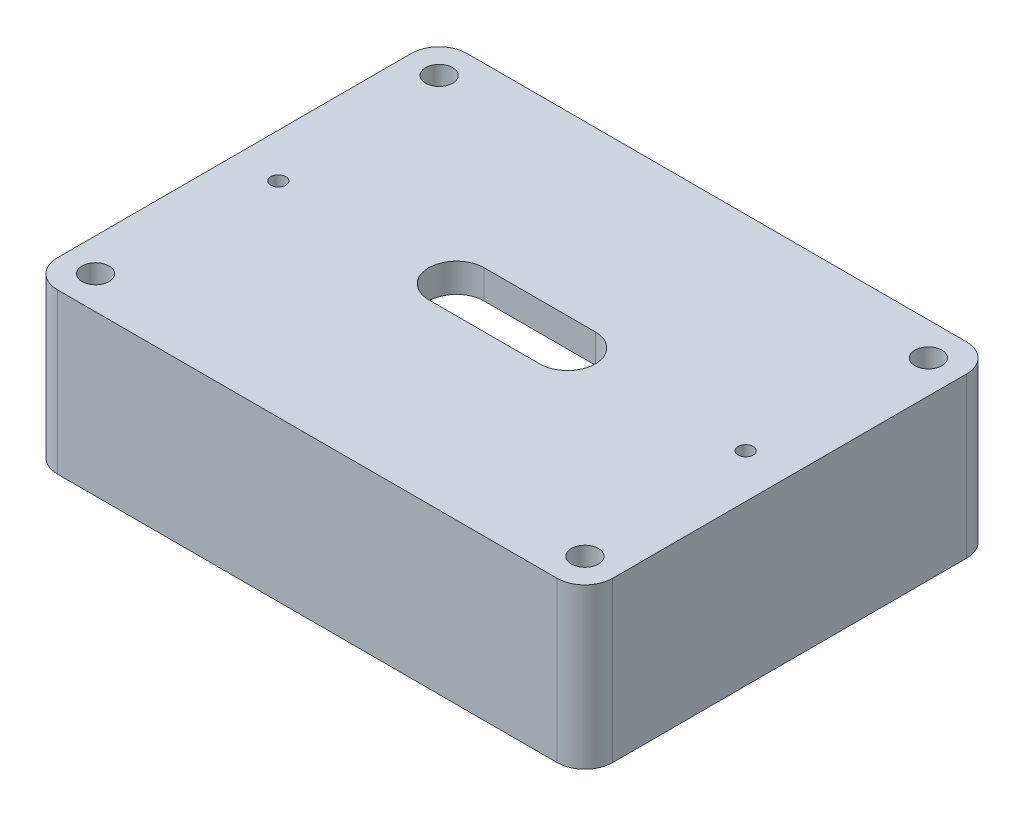
SolidWorks part; units mm, degrees
ref_plane "Front Plane" through (0, 0, 0) normal (0, 0, 1) x (1, 0, 0)
ref_plane "Top Plane" through (0, 0, 0) normal (0, 1, 0) x (1, 0, 0)
ref_plane "Right Plane" through (0, 0, 0) normal (1, 0, 0) x (0, 0, -1)
sketch "Sketch1" plane through (0, 0, 0) normal (0, 1, 0) x (1, 0, 0)
  line L1 (-40, -29.5) -> (40, -29.5)
  line L2 (-40, -29.5) -> (-40, 29.5)
  line L3 (-40, 29.5) -> (40, 29.5)
  line L4 (40, -29.5) -> (40, 29.5)
  line L5 (-40, -29.5) -> (40, 29.5) construction
  line L6 (-40, 29.5) -> (40, -29.5) construction
  point P0 (0, 0)
  dimension "D1" = 80
  dimension "D2" = 59
extrude "Boss-Extrude1" add sketch "Sketch1" along normal blind 23
sketch "Sketch2" plane through (0, 23, 0) normal (0, 1, 0) x (1, 0, 0)
  line L0 (40, -29.5) -> (40, 29.5) construction
  line L1 (40, 29.5) -> (-40, 29.5) construction
  line L2 (-40, -29.5) -> (40, -29.5) construction
  line L3 (-40, 29.5) -> (-40, -29.5) construction
  circle A0 centre (35.25, 24.75) radius 1.95
  circle A1 centre (35.25, -24.75) radius 1.95
  circle A2 centre (-35.25, 24.75) radius 1.95
  circle A3 centre (-35.25, -24.75) radius 1.95
  dimension "D1" = 4.75
  dimension "D4" = 4.75
  dimension "D7" = 4.75
  dimension "D10" = 4.75
  dimension "D3" = 4.75
  dimension "D5" = 4.75
  dimension "D8" = 4.75
  dimension "D11" = 4.75
extrude "Cut-Extrude1" cut sketch "Sketch2" against normal blind 23
shell "Shell2" thickness 4.15
sketch "Sketch3" plane through (0, 23, 0) normal (0, 1, 0) x (1, 0, 0)
  line L0 (8, 0) -> (-8, 0) construction
  line L1 (8, -4) -> (-8, -4)
  line L2 (8, 4) -> (-8, 4)
  line L3 (40, -29.5) -> (40, 29.5) construction
  line L4 (-40, 29.5) -> (-40, -29.5) construction
  arc A0 (8, -4) -> (8, 4) centre (8, 0) ccw
  arc A1 (-8, 4) -> (-8, -4) centre (-8, 0) ccw
  point P3 (0, 0)
  dimension "D1" = 32
  dimension "D2" = 32
extrude "Cut-Extrude2" cut sketch "Sketch3" against normal blind 23
sketch "Sketch4" plane through (-40, 0, 0) normal (-1, 0, 0) x (0, 0, 1)
  line L5 (-29.5, 23) -> (29.5, 23) construction
  line L6 (5, 0) -> (-5, 0)
  line L10 (5, 0) -> (5, 3)
  line L11 (5, 3) -> (-5, 3)
  line L12 (-5, 0) -> (-5, 3)
  line L13 (5, 0) -> (-5, 3) construction
  line L14 (5, 3) -> (-5, 0) construction
  line L15 (-29.5, 23) -> (-29.5, 0) construction
  line L16 (29.5, 23) -> (29.5, 0) construction
  point P0 (0, 1.5)
  dimension "D1" = 10
  dimension "D2" = 3
  dimension "D3" = 20
  dimension "D4" = 24.5
  dimension "D5" = 24.5
extrude "Cut-Extrude3" cut sketch "Sketch4" against normal blind 23
fillet "Fillet1" radius 4 4 edges at (40, 11.5, -29.5) (40, 11.5, 29.5) (-40, 11.5, 29.5) (-40, 11.5, -29.5)
fillet "Fillet2" radius 3 3 edges at (-40, 1.5, -5) (-40, 1.5, 5) (-40, 3, 0)
sketch "Sketch5" plane through (0, 23, 0) normal (0, 1, 0) x (1, 0, 0)
  line L0 (-36, -29.5) -> (36, -29.5) construction
  line L1 (40, -25.5) -> (40, 25.5) construction
  line L2 (-40, 25.5) -> (-40, -25.5) construction
  circle A0 centre (33.67, 0) radius 1.08
  circle A1 centre (-33.67, 0) radius 1.08
  dimension "D1" = 29.5
  dimension "D2" = 6.33
  dimension "D3" = 29.5
  dimension "D4" = 6.33
extrude "Cut-Extrude4" cut sketch "Sketch5" against normal blind 10
sketch "Sketch6" plane through (0, 0, 0) normal (0, -1, 0) x (-1, 0, 0)
  line L5 (-36, 29.5) -> (36, 29.5) construction
  line L6 (38.25, 9) -> (35.85, 9)
  line L13 (38.25, 9) -> (38.25, -9)
  line L14 (38.25, -9) -> (35.85, -9)
  line L15 (35.85, 9) -> (35.85, -9)
  line L16 (40, 25.5) -> (40, 8) construction
  line L17 (36, -29.5) -> (-36, -29.5) construction
  dimension "D1" = 20.5
  dimension "D2" = 18
  dimension "D3" = 2.4
  dimension "D4" = 1.75
  dimension "D5" = 20.5
extrude "Cut-Extrude5" cut sketch "Sketch6" against normal blind 18.85
